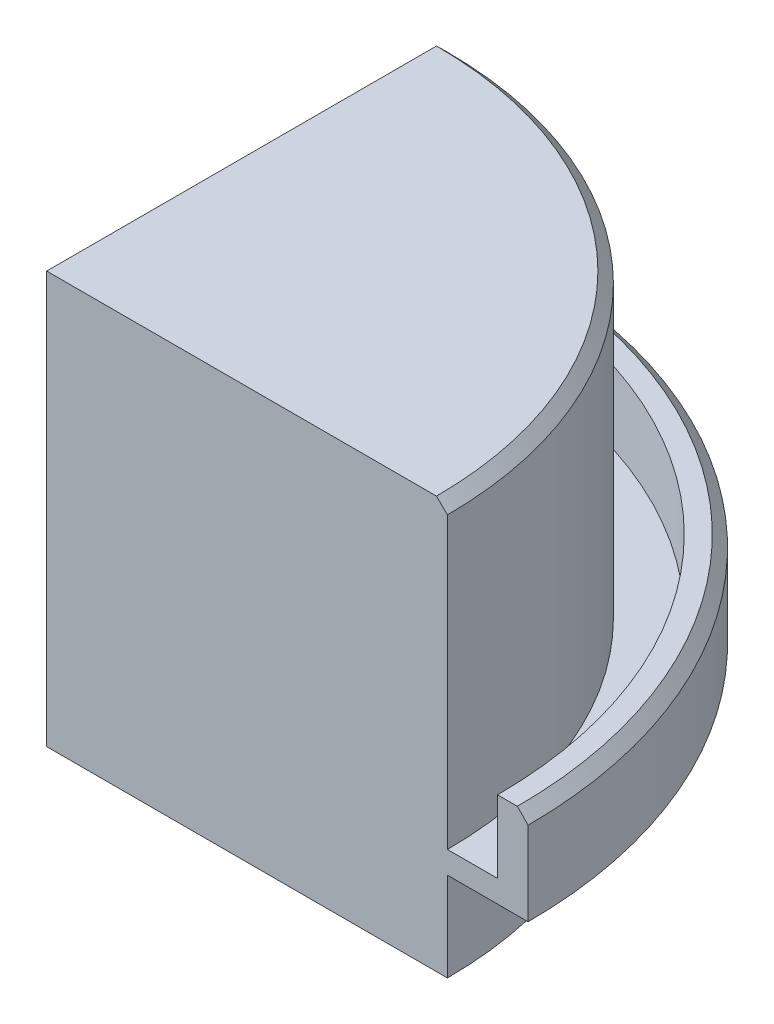
SolidWorks part; units mm, degrees
ref_plane "Front Plane" through (0, 0, 0) normal (0, 0, 1) x (1, 0, 0)
ref_plane "Top Plane" through (0, 0, 0) normal (0, 1, 0) x (1, 0, 0)
ref_plane "Right Plane" through (0, 0, 0) normal (1, 0, 0) x (0, 0, -1)
sketch "Sketch2" plane through (0, 0, 0) normal (0, 1, 0) x (1, 0, 0)
  line L0 (0, 0) -> (0, 21.971)
  line L1 (0, 0) -> (21.971, 0)
  arc A0 (0, 21.971) -> (21.971, 0) centre (0, 0) cw
  dimension "D1" = 21.971
extrude "Boss-Extrude3" add sketch "Sketch2" along normal blind 18.796
sketch "Sketch4" plane through (0, 18.796, 0) normal (0, 1, 0) x (1, 0, 0)
  line L0 (0, 0) -> (21.971, 0) construction
  line L1 (0, 21.971) -> (0, 0) construction
  line L2 (18.288, 0) -> (21.971, 0)
  line L3 (0, 18.288) -> (0, 21.971)
  arc A0 (18.288, 0) -> (0, 18.288) centre (0, 0) ccw
  arc A1 (21.971, 0) -> (0, 21.971) centre (0, 0) ccw
  dimension "D1" = 18.288
extrude "Cut-Extrude1" cut sketch "Sketch4" against normal blind 10.414
sketch "Sketch5" plane through (0, 0, 0) normal (0, -1, 0) x (1, 0, 0)
  line L0 (0, -21.971) -> (0, 0) construction
  line L1 (0, 0) -> (21.971, 0) construction
  arc A0 (21.971, 0) -> (0, -21.971) centre (0, 0) cw
  arc A1 (0, -21.971) -> (21.971, 0) centre (0, 0) ccw construction
  arc A2 (0, -18.288) -> (18.288, 0) centre (0, 0) ccw
  dimension "D1" = 18.288
extrude "Cut-Extrude-Thin1" cut sketch "Sketch5" against normal blind 4.064 thin
sketch "Sketch6" plane through (0, 8.382, 0) normal (0, 1, 0) x (1, 0, 0)
  line L0 (18.288, 0) -> (21.971, 0) construction
  line L1 (0, 21.971) -> (0, 18.288) construction
  line L2 (0, 18.288) -> (0, 20.574)
  line L3 (18.288, 0) -> (20.574, 0)
  arc A0 (20.574, 0) -> (0, 20.574) centre (0, 0) ccw
  arc A1 (18.288, 0) -> (0, 18.288) centre (0, 0) ccw
  dimension "D1" = 20.574
extrude "Cut-Extrude2" cut sketch "Sketch6" against normal blind 3.302
chamfer "Chamfer1" distance 0.5 angle 44.5 2 edges at (12.9316, 18.796, -12.9316) (15.5358, 8.382, -15.5358)
